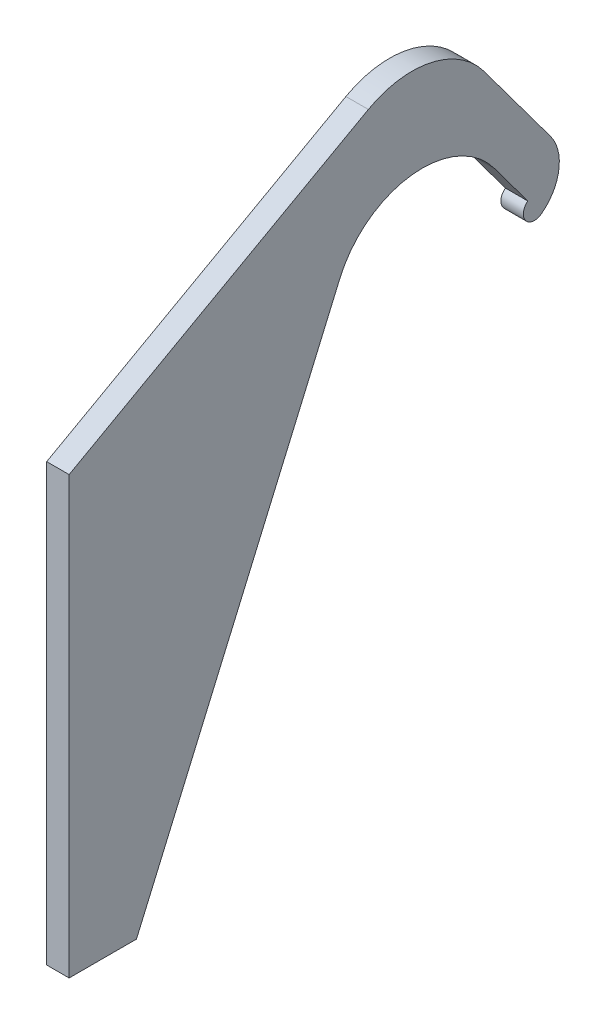
SolidWorks part; units mm, degrees
ref_plane "Front Plane" through (0, 0, 0) normal (0, 0, 1) x (1, 0, 0)
ref_plane "Top Plane" through (0, 0, 0) normal (0, 1, 0) x (1, 0, 0)
ref_plane "Right Plane" through (0, 0, 0) normal (1, 0, 0) x (0, 0, -1)
sketch "Sketch1" plane through (0, 0, 0) normal (1, 0, 0) x (0, 0, -1)
  line L0 (0, 0) -> (9.525, 0)
  line L1 (9.525, 0) -> (38.3222, 66.5955)
  line L2 (60.1728, 69.1297) -> (64.907, 62.7586)
  line L3 (68.1102, 69.0944) -> (58.7097, 81.7451)
  line L4 (42.3375, 85.2661) -> (0, 61.6912)
  line L5 (0, 61.6912) -> (0, 0)
  line L6 (49.979, 61.5549) -> (65.8539, 61.4844) construction
  line L7 (49.979, 61.5549) -> (54.3406, 23.9473) construction
  arc A0 (38.3222, 66.5955) -> (60.1728, 69.1297) centre (49.979, 61.5549) cw
  arc A1 (64.907, 62.7586) -> (66.8007, 60.2101) centre (65.8539, 61.4844) ccw
  arc A2 (66.8007, 60.2101) -> (68.1102, 69.0944) centre (63.0133, 65.307) ccw
  arc A3 (58.7097, 81.7451) -> (42.3375, 85.2661) centre (48.5159, 74.1703) ccw
  point P14 (54.3406, 23.9473)
  dimension "D1" = 60
  dimension "D2" = 1.5875
  dimension "D4" = 6.35
  dimension "D7" = 12.7
  dimension "D3" = 6.35
  dimension "D5" = 9.525
  dimension "D6" = 15.875
  dimension "D8" = 30
extrude "Boss-Extrude1" add sketch "Sketch1" along normal blind 3.175
